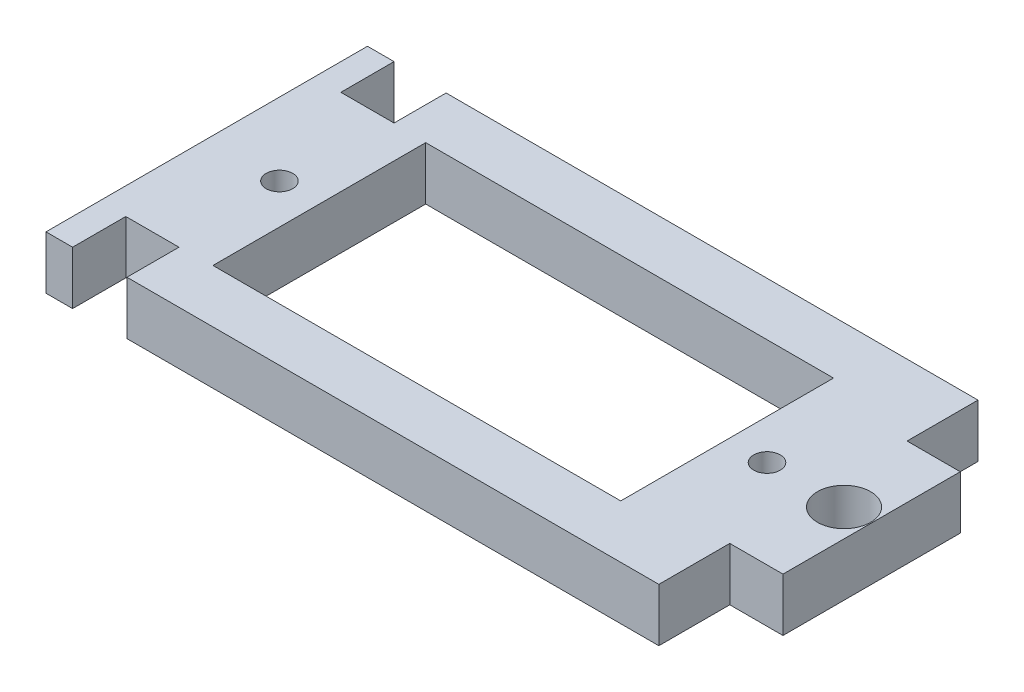
SolidWorks part; units mm, degrees
ref_plane "前视基准面" through (0, 0, 0) normal (0, 0, 1) x (1, 0, 0)
ref_plane "上视基准面" through (0, 0, 0) normal (0, 1, 0) x (1, 0, 0)
ref_plane "右视基准面" through (0, 0, 0) normal (1, 0, 0) x (0, 0, -1)
other "Configuration Table"
sketch "草图1" plane through (0, 0, 0) normal (0, 1, 0) x (1, 0, 0)
  line L0 (-15.0163, 6) -> (-15.0163, -3)
  line L1 (-15.0163, -3) -> (-13.5163, -3)
  line L2 (-13.5163, -3) -> (-13.5163, 0)
  line L3 (-13.5163, 0) -> (-10.5163, 0)
  line L4 (-10.5163, 0) -> (-10.5163, -2.9348)
  line L5 (-10.5163, -2.9348) -> (19.4837, -2.9348)
  line L6 (19.4837, -2.9348) -> (19.4837, 1.0652)
  line L7 (19.4837, 1.0652) -> (22.4837, 1.0652)
  line L8 (22.4837, 1.0652) -> (22.4837, 11.0652)
  line L9 (22.4837, 6.0652) -> (20.9837, 6.0652) construction
  line L10 (20.9837, 6.0652) -> (16.5837, 6.0652) construction
  line L11 (16.5837, 6.0652) -> (-10.9163, 6.0652) construction
  line L12 (-10.9163, 6.0652) -> (-8.6663, 6.0652) construction
  line L13 (-8.6663, 12.0652) -> (-8.6663, 0.0652)
  line L14 (-8.6663, 0.0652) -> (14.3337, 0.0652)
  line L15 (14.3337, 0.0652) -> (14.3337, 12.0652)
  line L16 (19.4837, 11.0652) -> (22.4837, 11.0652)
  line L17 (19.4837, 15.0652) -> (19.4837, 11.0652)
  line L18 (-8.6663, 12.0652) -> (14.3337, 12.0652)
  line L19 (-10.5163, 15.0652) -> (19.4837, 15.0652)
  line L20 (-10.5163, 12.1304) -> (-10.5163, 15.0652)
  line L21 (-15.0163, 15.1304) -> (-13.5163, 15.1304)
  line L22 (-13.5163, 15.1304) -> (-13.5163, 12.1304)
  line L23 (-13.5163, 12.1304) -> (-10.5163, 12.1304)
  line L24 (-15.0163, 6.1304) -> (-15.0163, 15.1304)
  line L25 (-15.0163, 6.1304) -> (-15.0163, 6)
  circle A1 centre (16.5837, 6.0652) radius 0.75
  circle A2 centre (-10.9163, 6.0652) radius 0.75
  circle A3 centre (20.9267, 6.0652) radius 1.5
  point P25 (14.3337, 6.0652)
  dimension "D1" = 9
  dimension "D2" = 1.5
  dimension "D3" = 3
  dimension "D4" = 3
  dimension "D5" = 30
  dimension "D6" = 4
extrude "凸台-拉伸3" add sketch "草图1" along normal blind 3 contours L24 L25 L0 L1 L2 L3 L4 L5 L6 L7 L8 L16 L17 L19 L20 L23 L22 L21 A3 A2 A1 L13 L18 L15 L14
